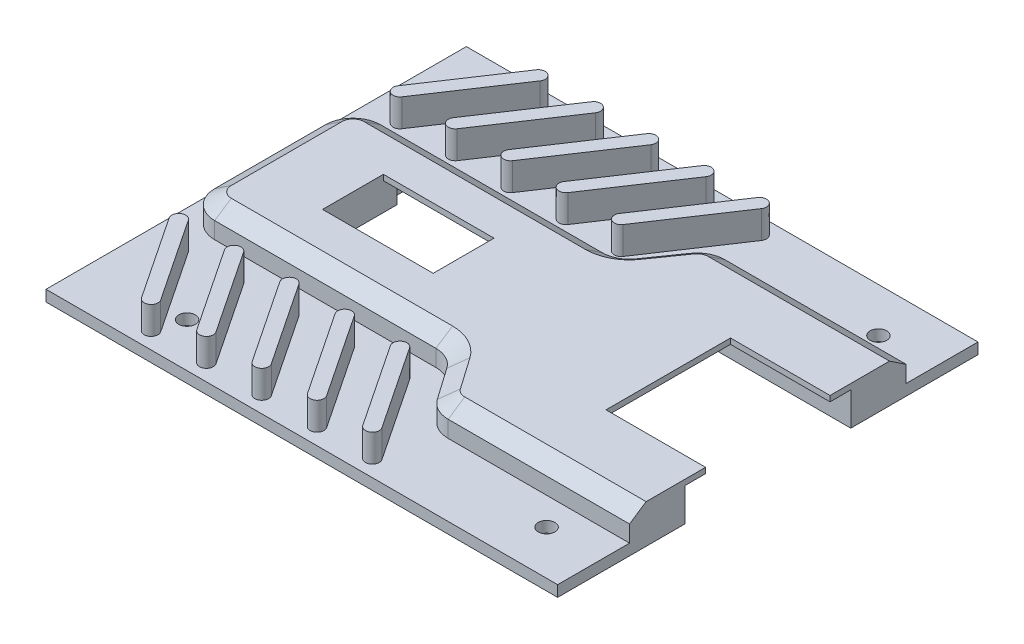
SolidWorks part; units mm, degrees
ref_plane "Front Plane" through (0, 0, 0) normal (0, 0, 1) x (1, 0, 0)
ref_plane "Top Plane" through (0, 0, 0) normal (0, 1, 0) x (1, 0, 0)
ref_plane "Right Plane" through (0, 0, 0) normal (1, 0, 0) x (0, 0, -1)
sketch "Sketch1" plane through (0, 0, 0) normal (0, 1, 0) x (1, 0, 0)
  line L1 (0, 0) -> (190, 0)
  line L2 (0, 0) -> (0, 160)
  line L3 (0, 160) -> (190, 160)
  line L4 (190, 0) -> (190, 160)
  dimension "D1" = 160
  dimension "D2" = 190
extrude "Boss-Extrude1" add sketch "Sketch1" along normal blind 4
sketch "Sketch2" plane through (0, 4, 0) normal (0, 1, 0) x (1, 0, 0)
  line L0 (10, 60) -> (10, 100)
  line L1 (20, 110) -> (68.3728, 110)
  line L2 (68.3728, 110) -> (100, 110)
  line L3 (108.1915, 114.2642) -> (116.224, 125.7358)
  line L4 (124.4155, 130) -> (190, 130)
  line L5 (190, 0) -> (190, 160) construction
  line L6 (20, 50) -> (100, 50)
  line L7 (108.1915, 45.7358) -> (116.224, 34.2642)
  line L8 (124.4155, 30) -> (190, 30)
  line L9 (190, 160) -> (0, 160) construction
  line L10 (0, 160) -> (0, 0) construction
  line L11 (0, 0) -> (190, 0) construction
  line L13 (97, 40) -> (77, 40)
  line L14 (77, 40) -> (57, 40)
  line L15 (57, 40) -> (37, 40)
  line L16 (37, 40) -> (17, 40)
  line L17 (37, 0) -> (37, 10)
  line L18 (37, 10) -> (57, 10)
  line L19 (57, 10) -> (77, 10)
  line L20 (77, 10) -> (97, 10)
  line L21 (97, 10) -> (117, 10)
  line L22 (17, 40) -> (37, 10) construction
  line L23 (19.0801, 41.3868) -> (39.0801, 11.3868)
  line L24 (14.9199, 38.6132) -> (34.9199, 8.6132)
  line L25 (37, 40) -> (57, 10) construction
  line L26 (39.0801, 41.3868) -> (59.0801, 11.3868)
  line L27 (34.9199, 38.6132) -> (54.9199, 8.6132)
  line L28 (57, 40) -> (77, 10) construction
  line L29 (59.0801, 41.3868) -> (79.0801, 11.3868)
  line L30 (54.9199, 38.6132) -> (74.9199, 8.6132)
  line L31 (77, 40) -> (97, 10) construction
  line L32 (79.0801, 41.3868) -> (99.0801, 11.3868)
  line L33 (74.9199, 38.6132) -> (94.9199, 8.6132)
  line L34 (97, 40) -> (117, 10) construction
  line L35 (99.0801, 41.3868) -> (119.0801, 11.3868)
  line L36 (94.9199, 38.6132) -> (114.9199, 8.6132)
  line L37 (0, 80) -> (204.0102, 80) construction
  line L38 (97, 120) -> (117, 150) construction
  line L39 (99.0801, 118.6132) -> (119.0801, 148.6132)
  line L40 (94.9199, 121.3868) -> (114.9199, 151.3868)
  line L41 (77, 120) -> (97, 150) construction
  line L42 (79.0801, 118.6132) -> (99.0801, 148.6132)
  line L43 (74.9199, 121.3868) -> (94.9199, 151.3868)
  line L44 (57, 120) -> (77, 150) construction
  line L45 (59.0801, 118.6132) -> (79.0801, 148.6132)
  line L46 (54.9199, 121.3868) -> (74.9199, 151.3868)
  line L47 (37, 120) -> (57, 150) construction
  line L48 (39.0801, 118.6132) -> (59.0801, 148.6132)
  line L49 (34.9199, 121.3868) -> (54.9199, 151.3868)
  line L50 (17, 120) -> (37, 150) construction
  line L51 (19.0801, 118.6132) -> (39.0801, 148.6132)
  line L52 (14.9199, 121.3868) -> (34.9199, 151.3868)
  arc A0 (19.0801, 41.3868) -> (14.9199, 38.6132) centre (17, 40) ccw
  arc A1 (34.9199, 8.6132) -> (39.0801, 11.3868) centre (37, 10) ccw
  arc A2 (39.0801, 41.3868) -> (34.9199, 38.6132) centre (37, 40) ccw
  arc A3 (54.9199, 8.6132) -> (59.0801, 11.3868) centre (57, 10) ccw
  arc A4 (59.0801, 41.3868) -> (54.9199, 38.6132) centre (57, 40) ccw
  arc A5 (74.9199, 8.6132) -> (79.0801, 11.3868) centre (77, 10) ccw
  arc A6 (79.0801, 41.3868) -> (74.9199, 38.6132) centre (77, 40) ccw
  arc A7 (94.9199, 8.6132) -> (99.0801, 11.3868) centre (97, 10) ccw
  arc A8 (99.0801, 41.3868) -> (94.9199, 38.6132) centre (97, 40) ccw
  arc A9 (114.9199, 8.6132) -> (119.0801, 11.3868) centre (117, 10) ccw
  arc A10 (124.4155, 130) -> (116.224, 125.7358) centre (124.4155, 120) ccw
  arc A11 (108.1915, 114.2642) -> (100, 110) centre (100, 120) cw
  arc A12 (20, 110) -> (10, 100) centre (20, 100) ccw
  arc A13 (10, 60) -> (20, 50) centre (20, 60) ccw
  arc A14 (116.224, 34.2642) -> (124.4155, 30) centre (124.4155, 40) ccw
  arc A15 (108.1915, 45.7358) -> (100, 50) centre (100, 40) ccw
  arc A16 (99.0801, 118.6132) -> (94.9199, 121.3868) centre (97, 120) cw
  arc A17 (114.9199, 151.3868) -> (119.0801, 148.6132) centre (117, 150) cw
  arc A18 (79.0801, 118.6132) -> (74.9199, 121.3868) centre (77, 120) cw
  arc A19 (94.9199, 151.3868) -> (99.0801, 148.6132) centre (97, 150) cw
  arc A20 (59.0801, 118.6132) -> (54.9199, 121.3868) centre (57, 120) cw
  arc A21 (74.9199, 151.3868) -> (79.0801, 148.6132) centre (77, 150) cw
  arc A22 (39.0801, 118.6132) -> (34.9199, 121.3868) centre (37, 120) cw
  arc A23 (54.9199, 151.3868) -> (59.0801, 148.6132) centre (57, 150) cw
  arc A24 (19.0801, 118.6132) -> (14.9199, 121.3868) centre (17, 120) cw
  arc A25 (34.9199, 151.3868) -> (39.0801, 148.6132) centre (37, 150) cw
  point P25 (27, 25)
  point P34 (47, 25)
  point P39 (67, 25)
  point P44 (87, 25)
  point P49 (107, 25)
  point P56 (119.2098, 130)
  point P59 (105.2057, 110)
  point P64 (10, 50)
  point P67 (119.2098, 30)
  point P75 (107, 135)
  point P82 (87, 135)
  point P89 (67, 135)
  point P96 (47, 135)
  point P103 (27, 135)
  line M10 (190, 0) -> (190, 160)
  dimension "D22" = 2.5
  dimension "D23" = 2.5
  dimension "D24" = 2.5
  dimension "0.25" = 2.5
  dimension "D26" = 2.5
  dimension "D27" = 10
  dimension "D8" = 90
  dimension "D29" = 10
  dimension "D1" = 10
  dimension "D2" = 30
  dimension "D3" = 30
  dimension "D4" = 125
  dimension "D5" = 125
  dimension "D6" = 50
  dimension "D7" = 50
  dimension "D9" = 90
  dimension "D10" = 70.7902
  dimension "D11" = 70.7902
  dimension "D12" = 20
  dimension "D13" = 20
  dimension "D14" = 20
  dimension "D15" = 20
  dimension "D16" = 10
  dimension "D17" = 10
  dimension "D18" = 20
  dimension "D19" = 20
  dimension "D20" = 20
  dimension "D21" = 20
  dimension "D28" = 3
  dimension "D30" = 90
  dimension "D31" = 7.6833
  dimension "D32" = 11.641
  dimension "D33" = 11.641
  dimension "D34" = 11.641
  dimension "D35" = 11.641
extrude "Boss-Extrude2" add sketch "Sketch2" along normal blind 10 contours A15 L7 A14 L8 L4 A10 L3 A11 L2 L1 A12 L0 A13 L6 M10 | L24 A1 L23 A0 | L27 A3 L26 A2 | L30 A5 L29 A4 | L33 A6 L32 A7 | L36 A9 L35 A8 | L39 A17 L40 A16 | L42 A19 L43 A18 | L45 A21 L46 A20 | L48 A23 L49 A22 | L51 A25 L52 A24
chamfer "Chamfer2" distance 4 distance2 6 13 edges at (157.2077, 14, -130) (119.798, 14, -128.8701) (112.2077, 14, -120) (104.6175, 14, -111.1299) (60, 14, -110) (12.9289, 14, -107.0711) (10, 14, -80) (12.9289, 14, -52.9289) (60, 14, -50) (104.6175, 14, -48.8701) (112.2077, 14, -40) (119.798, 14, -31.1299) (157.2077, 14, -30)
sketch "Sketch3" plane through (0, 4, 0) normal (0, 1, 0) x (1, 0, 0)
  line L0 (0, 160) -> (0, 0) construction
  line L1 (190, 0) -> (0, 0)
  line L2 (190, 0) -> (190, 4)
  line L3 (190, 4) -> (0, 4)
  line L4 (0, 0) -> (0, 4)
  line L5 (190, 160) -> (0, 160) construction
  line L6 (0, 4) -> (5, 4)
  line L7 (0, 4) -> (0, 160)
  line L8 (0, 160) -> (5, 160)
  line L9 (5, 4) -> (5, 160)
  line L10 (190, 130) -> (190, 160) construction
  line L11 (0, 160) -> (190, 160)
  line L12 (0, 160) -> (0, 156)
  line L13 (0, 156) -> (190, 156)
  line L14 (190, 160) -> (190, 156)
  dimension "D1" = 4
  dimension "D2" = 5
  dimension "D3" = 4
extrude "Cut-Extrude1" cut sketch "Sketch3" against normal blind 10 contours L14 L11 L9 L13 | L13 L7 L3 L9 | L7 L13 L9 L8
sketch "Sketch4" plane through (0, 14, 0) normal (0, 1, 0) x (1, 0, 0)
  line L0 (20, 110) -> (20, 104) construction
  line L1 (40, 91) -> (80, 91)
  line L2 (40, 91) -> (40, 69)
  line L3 (40, 69) -> (80, 69)
  line L4 (80, 91) -> (80, 69)
  line L5 (100, 110) -> (100, 104) construction
  line L6 (20, 56) -> (100, 56) construction
  line L7 (100, 104) -> (20, 104) construction
  dimension "D1" = 20
  dimension "D2" = 20
  dimension "D3" = 13
  dimension "D4" = 13
  dimension "D5" = 22
  dimension "D6" = 40
extrude "Cut-Extrude2" cut sketch "Sketch4" against normal blind 20
sketch "Sketch5" plane through (0, 0, 0) normal (0, -1, 0) x (1, 0, 0)
  line L0 (40, -91) -> (80, -91) construction
  line L1 (85, -64) -> (35, -64)
  line L2 (85, -64) -> (85, -96)
  line L3 (85, -96) -> (35, -96)
  line L4 (35, -64) -> (35, -96)
  line L5 (40, -69) -> (40, -91) construction
  line L6 (80, -69) -> (40, -69) construction
  line L7 (80, -91) -> (80, -69) construction
  dimension "D1" = 5
  dimension "D2" = 5
  dimension "D3" = 5
  dimension "D4" = 5
extrude "Cut-Extrude3" cut sketch "Sketch5" against normal blind 2
sketch "Sketch6" plane through (0, 0, 0) normal (0, -1, 0) x (-1, 0, 0)
  line L1 (-85, 96) -> (-35, 96)
  line L2 (-85, 96) -> (-85, 106)
  line L3 (-85, 106) -> (-35, 106)
  line L4 (-35, 96) -> (-35, 106)
  line L5 (-35, 64) -> (-85, 64)
  line L6 (-35, 64) -> (-35, 54)
  line L7 (-35, 54) -> (-85, 54)
  line L8 (-85, 64) -> (-85, 54)
  dimension "D1" = 10
  dimension "D2" = 50
  dimension "D3" = 50
  dimension "D4" = 10
extrude "Cut-Extrude5" cut sketch "Sketch6" against normal blind 12
sketch "Sketch8" plane through (0, 0, -91) normal (0, 0, 1) x (1, 0, 0)
  line L0 (80, 2) -> (80, 14) construction
  line L5 (80, 14) -> (80, 12)
  line L6 (40, 2) -> (40, 14) construction
  line L7 (80, 2) -> (40, 2)
  line L8 (80, 2) -> (80, 12)
  line L9 (80, 12) -> (40, 12)
  line L10 (40, 2) -> (40, 12)
  line M6 (40, 14) -> (40, 2)
  line M7 (40, 2) -> (80, 2)
  line M8 (80, 2) -> (80, 14)
  dimension "D1" = 2
  dimension "D2" = 10
extrude "Cut-Extrude7" cut sketch "Sketch8" against normal blind 10 contours L9 M8 M6 M7
sketch "Sketch9" plane through (0, 0, -69) normal (0, 0, -1) x (-1, 0, 0)
  line L0 (-40, 2) -> (-40, 14) construction
  line L1 (-80, 2) -> (-40, 2)
  line L2 (-80, 2) -> (-80, 12)
  line L3 (-80, 12) -> (-40, 12)
  line L4 (-40, 2) -> (-40, 12)
  dimension "D1" = 10
extrude "Cut-Extrude8" cut sketch "Sketch9" against normal blind 10
sketch "Sketch10" plane through (0, 14, 0) normal (0, 1, 0) x (1, 0, 0)
  line L0 (190, 36) -> (190, 124) construction
  line L1 (190, 57.5) -> (154, 57.5)
  line L2 (190, 57.5) -> (190, 102.5)
  line L3 (190, 102.5) -> (154, 102.5)
  line L4 (154, 57.5) -> (154, 102.5)
  line L5 (40, 80) -> (183.6608, 80) construction
  line L6 (40, 91) -> (40, 69) construction
  dimension "D1" = 36
  dimension "D2" = 45
  dimension "D3" = 22.5
extrude "Cut-Extrude9" cut sketch "Sketch10" against normal blind 30
sketch "Sketch11" plane through (0, 0, 0) normal (0, -1, 0) x (1, 0, 0)
  line L0 (190, -102.5) -> (190, -156) construction
  line L1 (190, -110) -> (140, -110)
  line L2 (190, -110) -> (190, -50)
  line L3 (190, -50) -> (140, -50)
  line L4 (140, -110) -> (140, -50)
  line L5 (190, -156) -> (5, -156) construction
  line L6 (190, -80) -> (102.2468, -80) construction
  dimension "D1" = 30
  dimension "D2" = 60
  dimension "D3" = 30
  dimension "D4" = 50
  dimension "D5" = 30
  dimension "D6" = 76
extrude "Cut-Extrude10" cut sketch "Sketch11" against normal blind 12
sketch "Sketch12" plane through (0, 4, 0) normal (0, 1, 0) x (1, 0, 0)
  line L0 (5, 4) -> (5, 156) construction
  line L1 (190, 130) -> (190, 156) construction
  line L2 (5, 156) -> (190, 156) construction
  line L3 (5, 80) -> (256.8746, 80) construction
  circle A0 centre (40, 140) radius 3
  circle A1 centre (170, 140) radius 3
  circle A2 centre (40, 20) radius 3
  circle A3 centre (170, 20) radius 3
  dimension "D1" = 35
  dimension "D2" = 6
  dimension "D3" = 20
  dimension "D4" = 6
  dimension "D5" = 16
  dimension "D6" = 16
  dimension "D7" = 165
extrude "Cut-Extrude11" cut sketch "Sketch12" against normal blind 10
